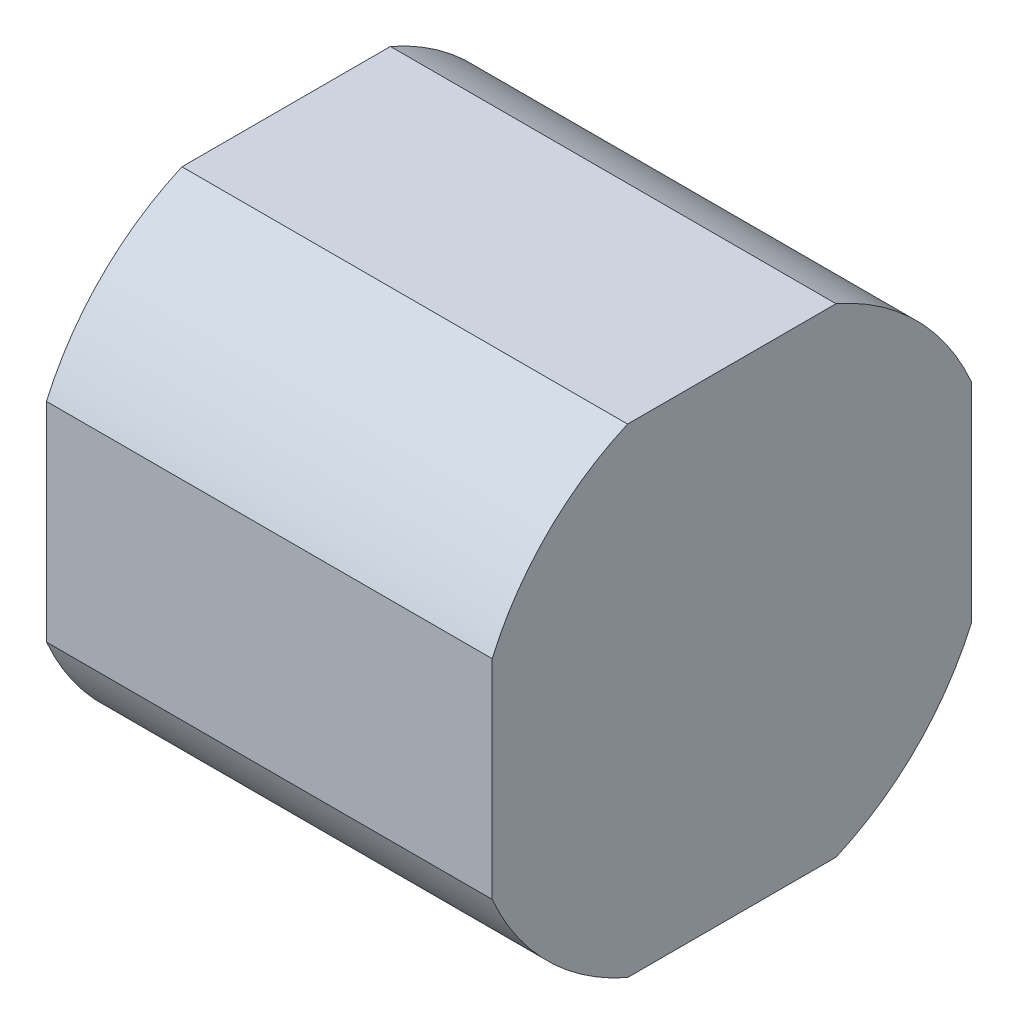
SolidWorks part; units mm, degrees
ref_plane "Front Plane" through (0, 0, 0) normal (1, 0, 0) x (0, 1, 0)
ref_plane "Top Plane" through (0, 0, 0) normal (0, 0, 1) x (0, 1, 0)
ref_plane "Right Plane" through (0, 0, 0) normal (0, 1, 0) x (-1, 0, 0)
sketch "Sketch1" plane through (0, 0, 0) normal (1, 0, 0) x (0, 1, 0)
  line L1 (-4.3267, 9.95) -> (4.3267, 9.95)
  line L2 (-9.95, 4.3267) -> (-9.95, -4.3267)
  line L3 (-4.3267, -9.95) -> (4.3267, -9.95)
  line L4 (9.95, 4.3267) -> (9.95, -4.3267)
  line L5 (-7.6721, 7.6721) -> (7.6721, -7.6721) construction
  line L6 (-7.6721, -7.6721) -> (7.6721, 7.6721) construction
  arc A0 (-4.3267, 9.95) -> (-9.95, 4.3267) centre (0, 0) ccw
  arc A1 (-9.95, -4.3267) -> (-4.3267, -9.95) centre (0, 0) ccw
  arc A2 (4.3267, -9.95) -> (9.95, -4.3267) centre (0, 0) ccw
  arc A3 (9.95, 4.3267) -> (4.3267, 9.95) centre (0, 0) ccw
  dimension "D1" = 21.7
  dimension "D2" = 19.9
extrude "Boss-Extrude1" add sketch "Sketch1" along normal blind 18.5
